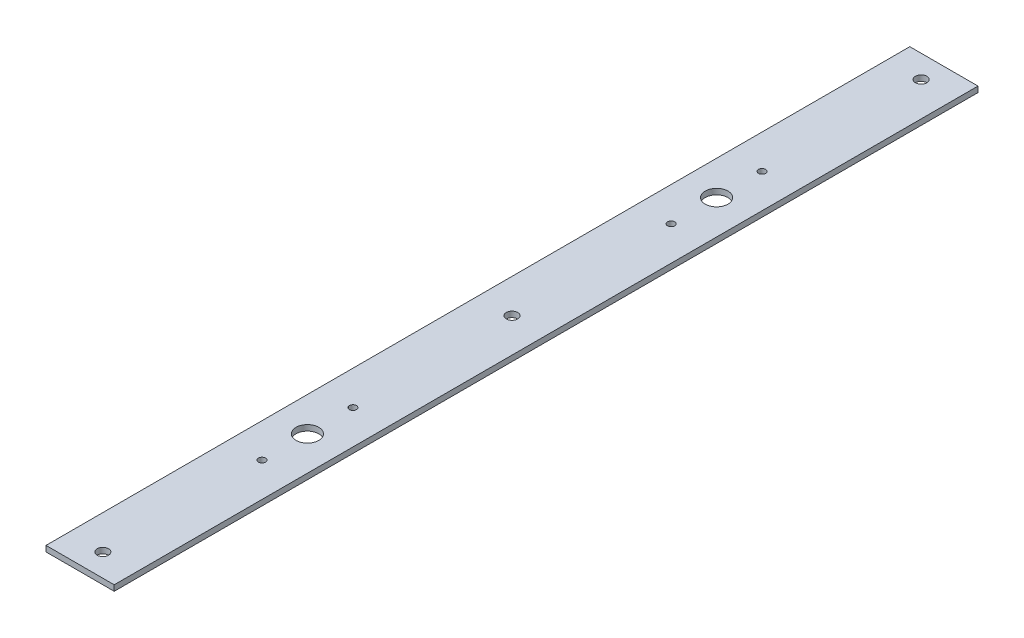
SolidWorks part; units mm, degrees
ref_plane "Front Plane" through (0, 0, 0) normal (0, 0, 1) x (1, 0, 0)
ref_plane "Top Plane" through (0, 0, 0) normal (0, 1, 0) x (1, 0, 0)
ref_plane "Right Plane" through (0, 0, 0) normal (1, 0, 0) x (0, 0, -1)
ref_plane "Plane1"
sketch "Sketch1" plane through (0, 0, 0) normal (0, 1, 0) x (-1, 0, 0)
  line L0 (-19.05, 241.3) -> (19.05, 241.3)
  line L1 (19.05, 241.3) -> (19.05, -241.3)
  line L2 (19.05, -241.3) -> (-19.05, -241.3)
  line L3 (-19.05, -241.3) -> (-19.05, 241.3)
  dimension "D1" = 38.1
  dimension "D2" = 482.6
extrude "Extrusion1" add sketch "Sketch1" along normal blind 3.175
hole_wizard "Hole1" positions "Sketch3" profile "Sketch2" legacy end condition through all
sketch "Sketch3" plane through (0, 3.175, 0) normal (0, 1, 0) x (1, 0, 0)
  point P1 (0, -228.6)
  point P2 (0, 228.6)
  point P3 (0, 0)
sketch "Sketch2" plane through (0, 3.175, 228.6) normal (1, 0, 0) x (0, 0, 1)
  line L0 (0, 0) -> (0, 3.175)
  line L1 (0, 3.175) -> (3.175, 3.175)
  line L2 (3.175, 3.175) -> (3.175, 0)
  line L3 (3.175, 0) -> (0, 0)
  line L4 (0, 110) -> (0, -10) construction
  dimension "Diameter" = 6.35
  dimension "Depth" = 3.175
hole_wizard "Hole2" positions "Sketch5" profile "Sketch4" legacy end condition through all
sketch "Sketch5" plane through (0, 3.175, 0) normal (0, 1, 0) x (1, 0, 0)
  point P1 (0, -101.6)
  point P2 (0, 101.6)
sketch "Sketch4" plane through (0, 3.175, 101.6) normal (1, 0, 0) x (0, 0, 1)
  line L0 (0, 0) -> (0, 3.175)
  line L1 (0, 3.175) -> (6.35, 3.175)
  line L2 (6.35, 3.175) -> (6.35, 0)
  line L3 (6.35, 0) -> (0, 0)
  line L4 (0, 110) -> (0, -10) construction
  dimension "Diameter" = 12.7
  dimension "Depth" = 3.175
ref_plane "Plane2"
sketch "Sketch6" plane through (0, 3.175, 0) normal (0, 1, 0) x (1, 0, 0)
  circle A0 centre (0, -101.6) radius 6.35
  circle A1 centre (0, 101.6) radius 6.35
extrude "Extrusion2" add sketch "Sketch6" against normal blind 3.175 contours A0 | A1
hole_wizard "Hole3" positions "Sketch8" profile "Sketch7" legacy end condition through all
sketch "Sketch8" plane through (0, 3.175, 0) normal (0, 1, 0) x (1, 0, 0)
  point P1 (0, 114.3)
  point P2 (0, -114.3)
sketch "Sketch7" plane through (0, 3.175, -114.3) normal (1, 0, 0) x (0, 0, 1)
  line L0 (0, 0) -> (0, 3.175)
  line L1 (0, 3.175) -> (6.35, 3.175)
  line L2 (6.35, 3.175) -> (6.35, 0)
  line L3 (6.35, 0) -> (0, 0)
  line L4 (0, 110) -> (0, -10) construction
  dimension "Diameter" = 12.7
  dimension "Depth" = 3.175
hole_wizard "Hole4" positions "Sketch10" profile "Sketch9" legacy end condition through all
sketch "Sketch10" plane through (0, 3.175, 0) normal (0, 1, 0) x (1, 0, 0)
  point P1 (0, -88.9)
  point P2 (0, -139.7)
  point P3 (0, 88.9)
  point P4 (0, 139.7)
sketch "Sketch9" plane through (0, 3.175, 88.9) normal (1, 0, 0) x (0, 0, 1)
  line L0 (0, 0) -> (0, 3.175)
  line L1 (0, 3.175) -> (1.9844, 3.175)
  line L2 (1.9844, 3.175) -> (1.9844, 0)
  line L3 (1.9844, 0) -> (0, 0)
  line L4 (0, 110) -> (0, -10) construction
  dimension "Diameter" = 3.9688
  dimension "Depth" = 3.175
